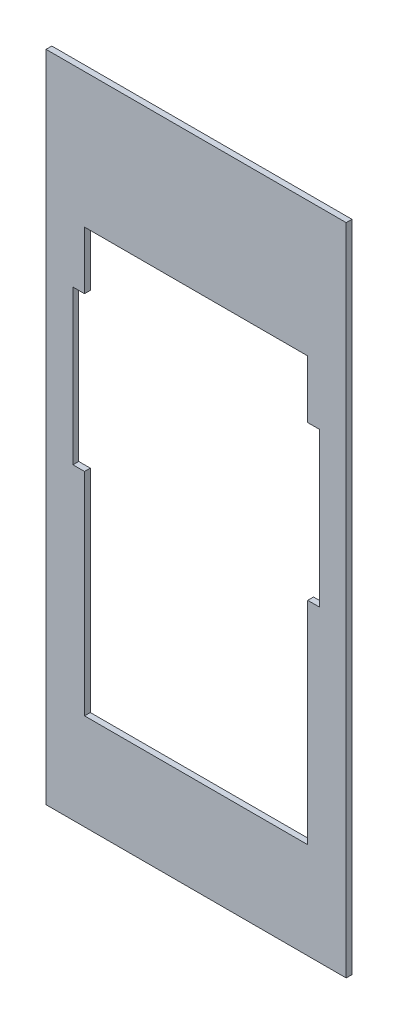
SolidWorks part; units mm, degrees
ref_plane "Front Plane" through (0, 0, 0) normal (0, 0, 1) x (1, 0, 0)
ref_plane "Top Plane" through (0, 0, 0) normal (0, 1, 0) x (1, 0, 0)
ref_plane "Right Plane" through (0, 0, 0) normal (1, 0, 0) x (0, 0, -1)
sketch "Sketch1" plane through (0, 0, 0) normal (0, 0, 1) x (1, 0, 0)
  line L1 (39, 85) -> (-39, 85)
  line L2 (39, 85) -> (39, -85)
  line L3 (39, -85) -> (-39, -85)
  line L4 (-39, 85) -> (-39, -85)
  line L5 (39, 85) -> (-39, -85) construction
  line L6 (39, -85) -> (-39, 85) construction
  line L20 (0, 0) -> (0, 85) construction
  line L21 (0, 0) -> (0, -85) construction
  line L23 (29, 50) -> (-29, 50)
  line L26 (-29, 50) -> (-29, 35)
  line L27 (-29, -60) -> (29, -60)
  line L33 (-29, 35) -> (-32, 35)
  line L35 (-29, -5) -> (-32, -5)
  line L36 (-32, 35) -> (-32, -5)
  line L37 (-29, -5) -> (-29, -60)
  line L38 (29, -5) -> (29, -60)
  line L39 (29, -5) -> (32, -5)
  line L40 (32, 35) -> (32, -5)
  line L41 (29, 35) -> (32, 35)
  line L42 (29, 50) -> (29, 35)
  point P0 (0, 0)
  point P8 (0, 0)
  dimension "D2" = 3
  dimension "D3" = 10
  dimension "D4" = 55
  dimension "D5" = 170
  dimension "D6" = 35
  dimension "D7" = 39
  dimension "D8" = 40
  dimension "D11" = 15
extrude "Boss-Extrude1" add sketch "Sketch1" along normal blind 1.5
